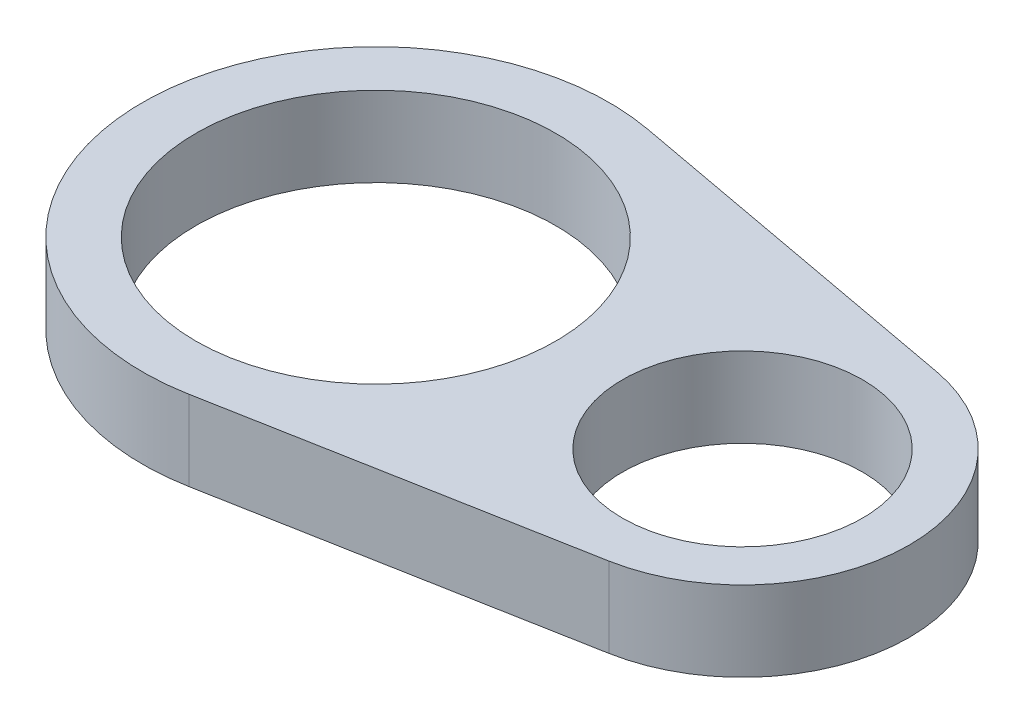
SolidWorks part; units mm, degrees
ref_plane "前视基准面" through (0, 0, 0) normal (0, 0, 1) x (1, 0, 0)
ref_plane "上视基准面" through (0, 0, 0) normal (0, 1, 0) x (1, 0, 0)
ref_plane "右视基准面" through (0, 0, 0) normal (1, 0, 0) x (0, 0, -1)
sketch "草图1" plane through (0, 0, 0) normal (0, 1, 0) x (1, 0, 0)
  circle A0 centre (0, 0) radius 27
  circle A1 centre (0, 0) radius 35
  dimension "D1" = 54
  dimension "D2" = 70
extrude "凸台-拉伸1" add sketch "草图1" along normal blind 12
sketch "草图2" plane through (0, 0, 0) normal (0, -1, 0) x (1, 0, 0)
  line L0 (6.3636, 34.4166) -> (59.5455, 24.5833)
  line L1 (6.3636, -34.4166) -> (59.5455, -24.5833)
  circle A1 centre (55, 0) radius 18
  arc A2 (59.5455, -24.5833) -> (59.5455, 24.5833) centre (55, 0) ccw
  arc A5 (6.3636, -34.4166) -> (6.3636, 34.4166) centre (0, 0) ccw
  dimension "D1" = 36
  dimension "D3" = 50
  dimension "D4" = 35
  dimension "D2" = 55
extrude "凸台-拉伸2" add sketch "草图2" against normal blind 12
